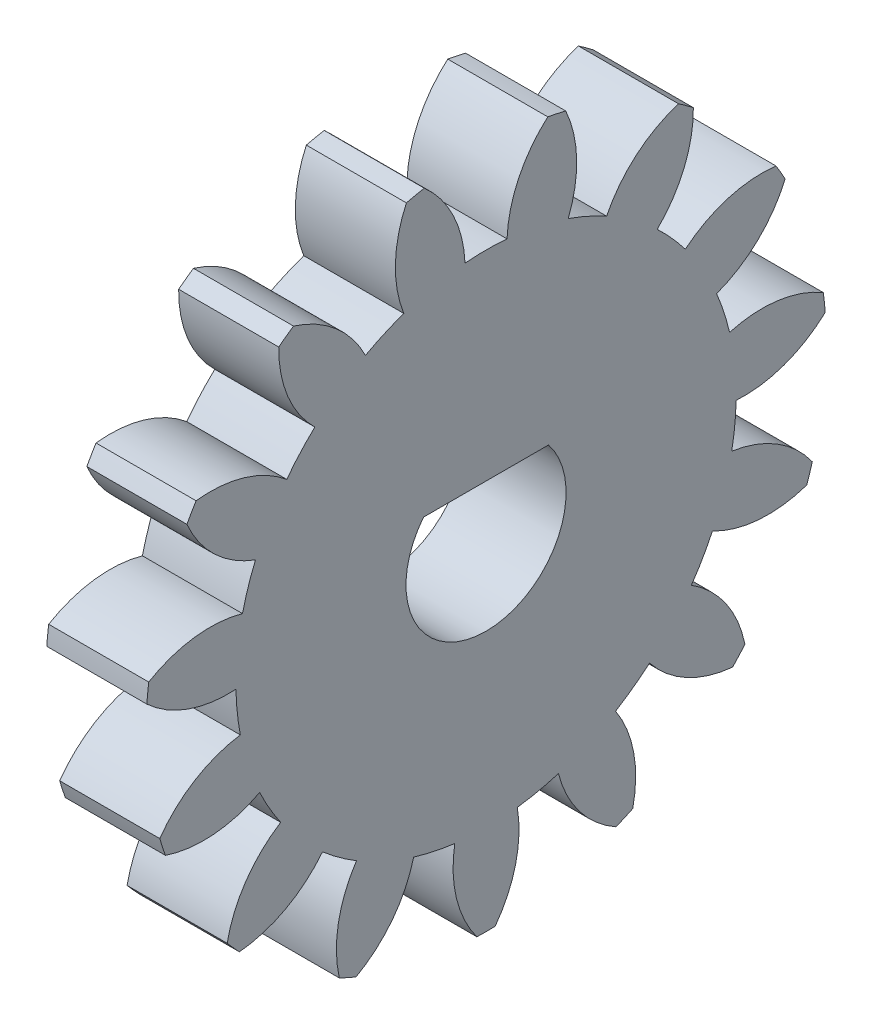
SolidWorks part; units mm, degrees
ref_plane "Plane1" through (0, 0, 0) normal (0, 0, 1) x (1, 0, 0)
ref_plane "Plane2" through (0, 0, 0) normal (0, 1, 0) x (1, 0, 0)
ref_plane "Plane3" through (0, 0, 0) normal (1, 0, 0) x (0, 0, -1)
sketch "HoldingSke" plane through (0, 0, 0) normal (0, 1, 0) x (1, 0, 0)
  line L0 (0, 0) -> (0.483, -0.1294)
  line L1 (-15, 0) -> (100, 0) construction
  line L2 (0, 0) -> (-2.1039, 2.3779)
  line L3 (0, 0) -> (-11.863, 4.5341)
  line L4 (0, 0) -> (8.3417, 2.2352)
  line L5 (0, 0) -> (-46.8476, -17.4728)
  line L6 (0, 0) -> (-4.1448, -2.7965)
  line L7 (-2.1039, 2.3779) -> (8.6586, 51.2059)
  line L8 (-76.2, 54.61) -> (-74.8, 54.61)
  line L9 (-71.009, 38.7566) -> (-53.1078, 45.2721)
  line L10 (-76.2, 71.12) -> (104.1128, 71.12)
  line L11 (0, 0) -> (-5, 0)
  line L12 (-76.2, 101.6) -> (-76.133, 101.6)
  line L13 (24.9733, 27.94) -> (52.9518, 28.4284)
  line L14 (24.9733, 27.94) -> (24.9743, 27.94)
  line L15 (24.9733, 27.94) -> (100.4006, 29.5858)
  line L16 (-63.627, -2) -> (-12.827, -2)
  circle A0 centre (0, 0) radius 4
  circle A1 centre (0, 0) radius 12.499
  circle A2 centre (0, 0) radius 37.5
  circle A3 centre (0, 0) radius 4
  dimension "MHD" = 24.998
  dimension "Hub_dia" = 75
  dimension "Bore" = 8
  dimension "MBD" = 8
  dimension "Num_teeth" = 15
  dimension "Pitch" = 0.5
  dimension "Overall_len" = 50
  dimension "Show_teeth" = 15
  dimension "Thickness" = 5
  dimension "OAL" = 50.0001
  dimension "T_dim" = 1.4
  dimension "Ap" = 20
  dimension "H" = 19.05
  dimension "Pitch_radius" = 180.3128
  dimension "Width" = 5
  dimension "Backlash" = 0.067
  dimension "Addendum_fac" = 1
  dimension "Dedendum_fac" = 1.25
  dimension "Clearance_fac" = 0.25
  dimension "Dedendum_add" = 0.001
  dimension "Module" = 2
sketch "BasProSke" plane through (0, 0, 0) normal (0, 1, 0) x (1, 0, 0)
  line L0 (-10, 0) -> (60, 0) construction
  line L1 (0, 0) -> (0, 17)
  line L2 (0, 0) -> (5, 0)
  line L3 (5, 0) -> (5, 17)
  line L4 (5, 17) -> (0, 17)
  dimension "Thickness" = 5
  dimension "Diameter" = 34
revolve "Base-Revolve" add sketch "BasProSke" angle 360 about L0
sketch "TooCutSke" plane through (0, 0, 0) normal (1, 0, 0) x (0, 0, -1)
  line L1 (0, 0) -> (0, 107) construction
  line L2 (0, 0) -> (-1.6851, 14.905) construction
  line L3 (0, 0) -> (-6.2081, 29.2069) construction
  line L4 (-1.6851, 14.905) -> (-3.1041, 14.6034) construction
  arc A0 (1.0501, 12.4548) -> (-1.0501, 12.4548) centre (0, 0) ccw
  arc A1 (3.1109, 16.7388) -> (-3.1109, 16.7388) centre (0, 0) ccw
  circle A2 centre (0, 0) radius 15 construction
  circle A3 centre (0, 0) radius 14.0954 construction
  arc A4 (-1.0501, 12.4548) -> (-3.1109, 16.7388) centre (-7.045, 12.2085) ccw
  arc A5 (3.1109, 16.7388) -> (1.0501, 12.4548) centre (7.045, 12.2085) ccw
  dimension "Root_dia" = 24.998
  dimension "Overcut_dia" = 34.0508
  dimension "Pitch_dia" = 30
  dimension "Base_dia" = 28.1908
  dimension "Flank_rad" = 6
  dimension "Half_ang" = 12
  dimension "Half_CT" = 1.4507
extrude "ToothCut" cut sketch "TooCutSke" along normal through all
fillet "Breaks" [suppressed] radius 0.04
fillet "RootFillets" [suppressed] radius 0.501
pattern_circular "TeethCuts" count 15 every 24 about axis through (-10, 0, 0) along (1, 0, 0) of "ToothCut", "RootFillets", "Breaks"
sketch "HubNeaOneSke" plane through (0, 0, 0) normal (-1, 0, 0) x (0, 0, 1)
  circle A0 centre (0, 0) radius 12.499
  dimension "Diameter" = 24.998
extrude "HubNearOne" [suppressed] add sketch "HubNeaOneSke" along normal blind 45.0001
sketch "HubNeaBotSke" plane through (0, 0, 0) normal (-1, 0, 0) x (0, 0, 1)
  circle A0 centre (0, 0) radius 12.499
  dimension "Diameter" = 24.998
extrude "HubNearBoth" [suppressed] add sketch "HubNeaBotSke" along normal blind 22.5
ref_plane "FarPln" through (5, 0, 0) normal (1, 0, 0) x (0, 0, -1)
sketch "HubFarSke" plane through (5, 0, 0) normal (1, 0, 0) x (0, 0, -1)
  circle A0 centre (0, 0) radius 12.499
  dimension "Diameter" = 24.998
extrude "HubFar" [suppressed] add sketch "HubFarSke" along normal blind 22.5
sketch "BorSke" plane through (0, 0, 0) normal (1, 0, 0) x (0, 0, -1)
  circle A0 centre (0, 0) radius 4
  dimension "Diameter" = 8
extrude "Bore" cut sketch "BorSke" along normal mid plane 100.0001
sketch "KeySke" plane through (0, 0, 0) normal (1, 0, 0) x (0, 0, -1)
  line L0 (-1.5, 0) -> (-1.5, 5.4)
  line L1 (-1.5, 5.4) -> (1.5, 5.4)
  line L2 (1.5, 5.4) -> (1.5, 0)
  line L3 (0, 0) -> (0, 34) construction
  line L4 (-1.5, 0) -> (1.5, 0)
  dimension "Offset" = 5.4
  dimension "Width" = 3
extrude "Keyway" [suppressed] cut sketch "KeySke" along normal mid plane 100.0001
pattern_circular "Keyway2" [suppressed] count 2 every 90 about axis through (-10, 0, 0) along (1, 0, 0)
sketch "Sketch1" plane through (5, 0, 0) normal (1, 0, 0) x (0, 0, -1)
  line L0 (3.1225, 2.5) -> (-3.1225, 2.5)
  circle A0 centre (0, 0) radius 4 construction
  arc A1 (3.1225, 2.5) -> (-3.1225, 2.5) centre (0, 0) ccw
  dimension "D1" = 2.5
extrude "Boss-Extrude1" add sketch "Sketch1" against normal blind 5
equation "' \"Module@HoldingSke\" = 6.35"
equation "' \"Num_teeth@HoldingSke\" = 12"
equation "' \"Ap@HoldingSke\" =  20"
equation "' \"Ap@HoldingSke\" = 20"
equation "' \"Width@HoldingSke\" = 0.5 * 25.4"
equation "' \"Hub_dia@HoldingSke\"= 1 * 25.4"
equation "' \"Hub_dia@HoldingSke\" = 1 * 25.4"
equation "' \"Overall_len@HoldingSke\" = 1.0 * 25.4"
equation "' \"Bore@HoldingSke\" = 0.75 * 25.4"
equation "' \"T_dim@HoldingSke\" = 0.1 * 25.4"
equation "' \"Width@KeySke\" = 0.25 * 25.4"
equation "' \"Show_teeth@HoldingSke\" = 13"
equation "' \"Backlash@HoldingSke\" = 0.009 * 25.4"
equation "' \"Addendum_fac@HoldingSke\" = 1.0"
equation "' \"Dedendum_fac@HoldingSke\" = 1.25"
equation "' \"Dedendum_add@HoldingSke\" = 0.00005 * 25.4"
equation "' \"Clearance_fac@HoldingSke\" = 0.25"
equation "\"Pitch@HoldingSke\" = 1 / \"Module@HoldingSke\""
equation "\"Overcut_dia@TooCutSke\" = (\"Num_teeth@HoldingSke\" + 2 * \"Addendum_fac@HoldingSke\") / \"Pitch@HoldingSke\" + 0.002 * 25.4"
equation "\"Pitch_dia@TooCutSke\" = \"Num_teeth@HoldingSke\" / \"Pitch@HoldingSke\""
equation "\"Base_dia@TooCutSke\" = \"Num_teeth@HoldingSke\" / \"Pitch@HoldingSke\" * cos((\"Ap@HoldingSke\"  * 3.14159265 / 180))"
equation "\"Root_dia@TooCutSke\" = (\"Num_teeth@HoldingSke\" + 2) / \"Pitch@HoldingSke\" - 2 * (\"Addendum_fac@HoldingSke\" + \"Dedendum_fac@HoldingSke\") / \"Pitch@HoldingSke\" - \"Dedendum_add@HoldingSke\" * 2"
equation "\"Half_ang@TooCutSke\" = 180 / \"Num_teeth@HoldingSke\""
equation "\"Half_CT@TooCutSke\" = \"Num_teeth@HoldingSke\" / \"Pitch@HoldingSke\" * sin((3.14159265 / 2 / \"Num_teeth@HoldingSke\")) / 2 - 7 * \"Backlash@HoldingSke\" / 4"
equation "\"Flank_rad@TooCutSke\" = \"Num_teeth@HoldingSke\" / \"Pitch@HoldingSke\" / 5"
equation "\"Radius@RootFillets\" = \"Clearance_fac@HoldingSke\" / \"Pitch@HoldingSke\" + \"Dedendum_add@HoldingSke\""
equation "\"Break_rad@Breaks\" = 0.02 / \"Pitch@HoldingSke\""
equation "\"Thickness@HoldingSke\" = \"Width@HoldingSke\""
equation "\"OAL@HoldingSke\" = \"Thickness@HoldingSke\""
equation "\"MHD@HoldingSke\" = (\"Num_teeth@HoldingSke\" + 2) / \"Pitch@HoldingSke\" - 2 * (\"Addendum_fac@HoldingSke\" + \"Dedendum_fac@HoldingSke\")  / \"Pitch@HoldingSke\" - \"Dedendum_add@HoldingSke\" * 2"
equation "\"MBD@HoldingSke\" = (\"Num_teeth@HoldingSke\" + 2) / \"Pitch@HoldingSke\" - 2 * (\"Addendum_fac@HoldingSke\" + \"Dedendum_fac@HoldingSke\")  / \"Pitch@HoldingSke\" - \"Dedendum_add@HoldingSke\" * 2 - 0.002 * 25.4"
equation "\"MHD@HoldingSke\" = ((sgn( \"MHD@HoldingSke\" - \"Hub_dia@HoldingSke\" )-1)*( \"MHD@HoldingSke\" - \"Hub_dia@HoldingSke\" ))/-2+ \"Hub_dia@HoldingSke\""
equation "\"MBD@HoldingSke\" = ((sgn( \"MBD@HoldingSke\" - \"Bore@HoldingSke\" )-1)*( \"MBD@HoldingSke\" - \"Bore@HoldingSke\" ))/-2+ \"Bore@HoldingSke\""
equation "\"OAL@HoldingSke\" = ((sgn( \"OAL@HoldingSke\" - \"Overall_len@HoldingSke\" )+1)*( \"OAL@HoldingSke\" - \"Overall_len@HoldingSke\" ))/2 + \"Overall_len@HoldingSke\" + 0.000002 * 25.4"
equation "\"Num_teeth@TeethCuts\" = int( \"Show_teeth@HoldingSke\" ) + 1"
equation "\"Num_teeth@TeethCuts\" = ((sgn( \"Num_teeth@TeethCuts\" - \"Num_teeth@HoldingSke\" )-1)*( \"Num_teeth@TeethCuts\" - \"Num_teeth@HoldingSke\" ))/-2+ \"Num_teeth@HoldingSke\""
equation "\"Num_teeth@TeethCuts\" = ((sgn( \"Num_teeth@TeethCuts\" - 2.0)+1)*( \"Num_teeth@TeethCuts\" - 2.0))/2 +2.0"
equation "\"Angle@TeethCuts\" = 360.0 / \"Num_teeth@HoldingSke\""
equation "\"Diameter@BasProSke\" = (\"Num_teeth@HoldingSke\" + 2 * \"Addendum_fac@HoldingSke\") / \"Pitch@HoldingSke\""
equation "\"Thickness@BasProSke\"  = \"Thickness@HoldingSke\""
equation "' \"Fillet_rad@BasProSke\" =  \"Thickness@HoldingSke\" * 0.05"
equation "' \"Fillet_rad@BasProSke\" = \"Thickness@HoldingSke\" * 0.05"
equation "\"MHD@HoldingSke\" = ((sgn( \"MHD@HoldingSke\" - \"Root_dia@TooCutSke\" )-1)*( \"MHD@HoldingSke\" - \"Root_dia@TooCutSke\" ))/-2+ \"Root_dia@TooCutSke\""
equation "\"Diameter@HubNeaOneSke\" = \"MHD@HoldingSke\""
equation "\"Length@HubNearOne\" = \"OAL@HoldingSke\" - \"Thickness@BasProSke\""
equation "\"Diameter@HubNeaBotSke\" = \"MHD@HoldingSke\""
equation "\"Length@HubNearBoth\" = ( \"OAL@HoldingSke\" - \"Thickness@BasProSke\" ) / 2.0"
equation "\"Thickness@FarPln\" = \"Thickness@BasProSke\""
equation "\"Diameter@HubFarSke\" = \"MHD@HoldingSke\""
equation "\"Length@HubFar\" = ( \"OAL@HoldingSke\" - \"Thickness@BasProSke\" ) / 2.0"
equation "\"Diameter@BorSke\" = \"MBD@HoldingSke\""
equation "\"D1@Bore\" = \"OAL@HoldingSke\" * 2.0"
equation "\"D1@Keyway\" = \"OAL@HoldingSke\" * 2.0"
equation "\"Offset@KeySke\" = \"T_dim@HoldingSke\" + \"MBD@HoldingSke\" / 2.0"
